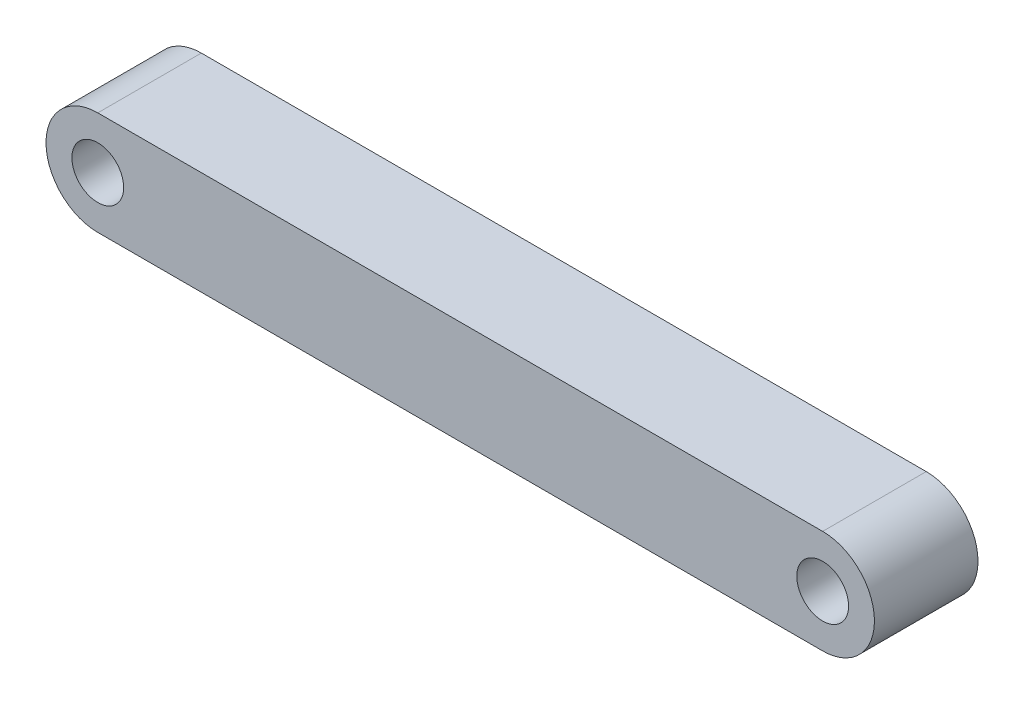
SolidWorks part; units mm, degrees
ref_plane "Front Plane" through (0, 0, 0) normal (0, 0, 1) x (1, 0, 0)
ref_plane "Top Plane" through (0, 0, 0) normal (0, 1, 0) x (1, 0, 0)
ref_plane "Right Plane" through (0, 0, 0) normal (1, 0, 0) x (0, 0, -1)
sketch "Sketch1" plane through (0, 0, 0) normal (0, 0, 1) x (1, 0, 0)
  line L0 (0, 0) -> (42, 0)
  line L1 (0, 6) -> (42, 6)
  arc A0 (0, 6) -> (0, 0) centre (0, 3) ccw
  arc A1 (42, 0) -> (42, 6) centre (42, 3) ccw
  circle A2 centre (0, 3) radius 1.5
  circle A3 centre (42, 3) radius 1.5
  dimension "D1" = 42
  dimension "D3" = 3
  dimension "D2" = 6
extrude "Boss-Extrude1" add sketch "Sketch1" along normal blind 6
